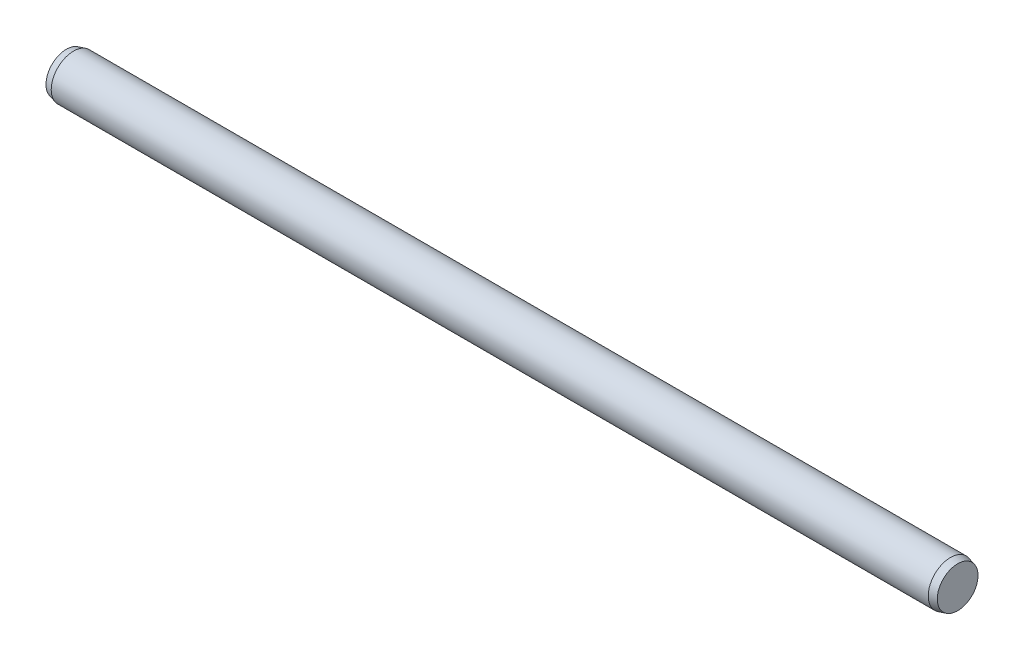
SolidWorks part; units mm, degrees
ref_plane "Front Plane" through (0, 0, 0) normal (0, 0, 1) x (1, 0, 0)
ref_plane "Top Plane" through (0, 0, 0) normal (0, 1, 0) x (1, 0, 0)
ref_plane "Right Plane" through (0, 0, 0) normal (1, 0, 0) x (0, 0, -1)
sketch "Sketch1" plane through (0, 0, 0) normal (0, 0, 1) x (1, 0, 0)
  line L0 (-49.2, 0) -> (49.2, 0) construction
  line L1 (49.2, 2.5) -> (49.2, -2.5) construction
  line L2 (-49.2, 2.5) -> (-49.2, -2.5) construction
  line L3 (50, 2.5) -> (50, -2.5) construction
  line L4 (-50, 2.5) -> (-50, -2.5) construction
  line L5 (-49.2, 0) -> (-50, 0) construction
  line L6 (49.2, 0) -> (50, 0) construction
  point P11 (45, 0)
  point P21 (-45, 0)
  dimension "Dia" = 5
  dimension "C" = 0.8
  dimension "D1" = 0.8
  dimension "Length" = 100
  dimension "D2" = 5
  dimension "D3" = 5
sketch "Sketch2" plane through (0, 0, 0) normal (1, 0, 0) x (0, 0, -1)
  circle A0 centre (0, 0) radius 2.5
extrude "Extrude1" add sketch "Sketch2" against normal up to vertex (49.2 mm away) and the other way up to vertex (49.2 mm away) up to point (-49.2, 2.5, 0) other way up to point (49.2, 2.5, 0)
sketch "Sketch3" plane through (49.2, 0, 0) normal (1, 0, 0) x (0, 0, -1)
  circle A1 centre (0, 0) radius 2.5
  circle A2 centre (0, 0) radius 2.5
  dimension "D1" = 0
extrude "Extrude2" add sketch "Sketch3" along normal up to vertex (0.8 mm away) draft 15 up to point (50, 0, 0)
sketch "Sketch4" plane through (-49.2, 0, 0) normal (-1, 0, 0) x (0, 0, 1)
  circle A1 centre (0, 0) radius 2.5
  circle A2 centre (0, 0) radius 2.5
  dimension "D1" = 0
extrude "Extrude3" add sketch "Sketch4" along normal up to vertex (0.8 mm away) draft 15 up to point (-50, 0, 0)
sketch "Sketch5" plane through (0, 0, 0) normal (1, 0, 0) x (0, 0, -1)
  line L0 (-2.5, 0) -> (2.5, 0) construction
  point P4 (0, 0)
  dimension "D1" = 5
equation "\"D1@Sketch1\" = \"C@Sketch1\""
equation "\"D1@Sketch5\" = \"Dia@Sketch1\""
equation "\"D2@Sketch1\"=\"Dia@Sketch1\""
equation "\"D3@Sketch1\"=\"D2@Sketch1\""
